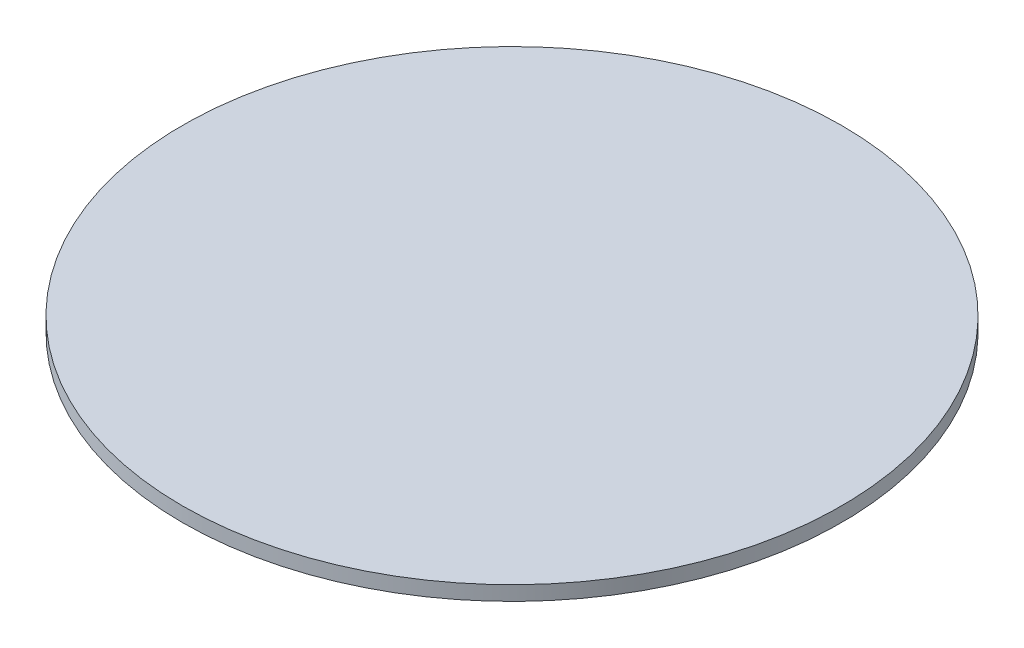
SolidWorks part; units mm, degrees
ref_plane "Front Plane" through (0, 0, 0) normal (0, 0, 1) x (1, 0, 0)
ref_plane "Top Plane" through (0, 0, 0) normal (0, 1, 0) x (1, 0, 0)
ref_plane "Right Plane" through (0, 0, 0) normal (1, 0, 0) x (0, 0, -1)
sketch "Sketch1" plane through (0, 0, 0) normal (0, 1, 0) x (1, 0, 0)
  circle A0 centre (0, 0) radius 25
  dimension "D1" = 50
extrude "Boss-Extrude1" add sketch "Sketch1" along normal blind 1.1
